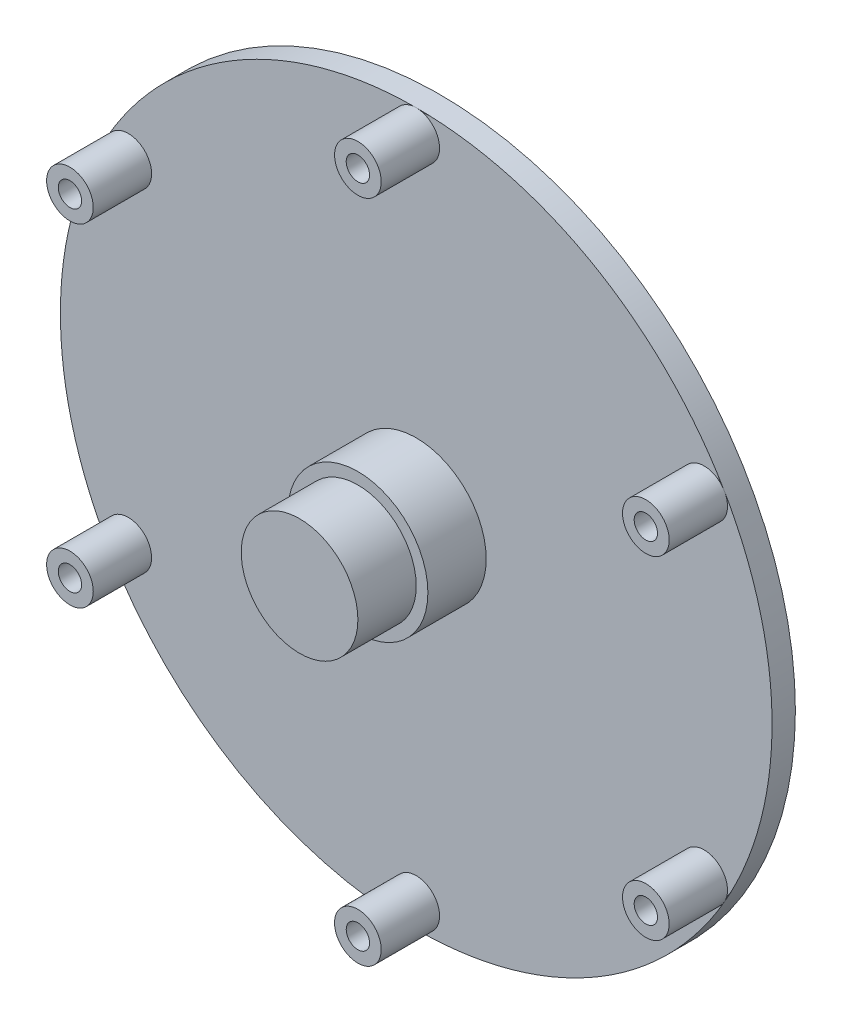
SolidWorks part; units mm, degrees
ref_plane "前视基准面" through (0, 0, 0) normal (0, 0, 1) x (1, 0, 0)
ref_plane "上视基准面" through (0, 0, 0) normal (0, 1, 0) x (1, 0, 0)
ref_plane "右视基准面" through (0, 0, 0) normal (1, 0, 0) x (0, 0, -1)
other "Configuration Table"
sketch "草图1" plane through (0, 0, 0) normal (0, 0, 1) x (1, 0, 0)
  circle A0 centre (0, 0) radius 30.5
  circle A1 centre (0, 28.5) radius 2 construction
extrude "凸台-拉伸1" add sketch "草图1" along normal blind 2 contours A0
sketch "草图2" plane through (0, 0, 2) normal (0, 0, 1) x (1, 0, 0)
  circle A0 centre (0, 28.5) radius 1
  dimension "D1" = 2
  dimension "D2" = 28.5
extrude "凸台-拉伸2" add sketch "草图2" along normal blind 1.5
pattern_circular "阵列(圆周)1" count 6 over 360 about axis through (0, 0, 0) along (0, 0, 1) of "凸台-拉伸2"
sketch "草图3" plane through (0, 0, 2) normal (0, 0, 1) x (1, 0, 0)
  circle A0 centre (0, 0) radius 5
  dimension "D1" = 10
extrude "凸台-拉伸3" add sketch "草图3" along normal blind 10 and the other way blind 20
sketch "草图4" plane through (0, 0, 2) normal (0, 0, 1) x (1, 0, 0)
  circle A0 centre (0, 28.5) radius 1
  circle A1 centre (0, 28.5) radius 1 construction
extrude "拉伸-薄壁1" add sketch "草图4" along normal blind 5 thin
pattern_circular "阵列(圆周)3" count 6 over 360 about axis through (0, 0, 0) along (0, 0, 1) of "拉伸-薄壁1"
sketch "草图5" plane through (0, 0, 0) normal (0, 0, -1) x (-1, 0, 0)
  circle A3 centre (0, 0) radius 6
  circle A4 centre (0, 0) radius 6
  dimension "D1" = 1
extrude "凸台-拉伸5" add sketch "草图5" along normal blind 1
sketch "草图6" plane through (0, 0, 2) normal (0, 0, 1) x (1, 0, 0)
  circle A2 centre (0, 0) radius 6
  circle A3 centre (0, 0) radius 6
  dimension "D1" = 1
extrude "凸台-拉伸6" add sketch "草图6" along normal blind 5
sketch "草图7" plane through (0, 0, -18) normal (0, 0, -1) x (-1, 0, 0)
  circle A0 centre (0, 0) radius 3
  dimension "D1" = 6
extrude "切除-拉伸1" cut sketch "草图7" against normal blind 8
